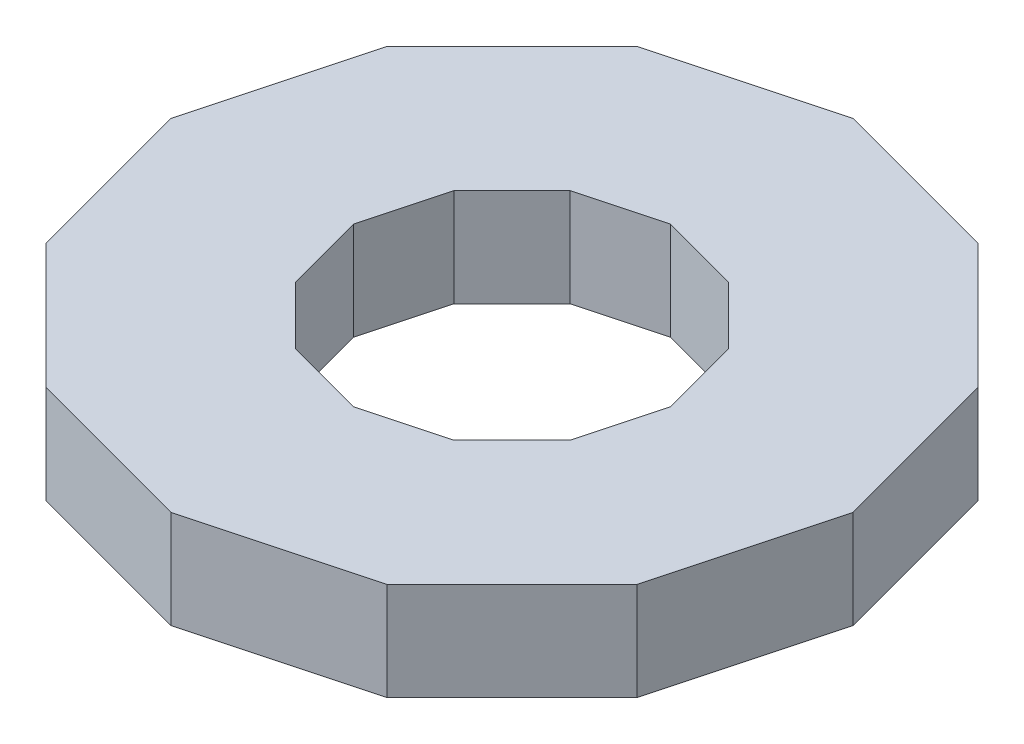
SolidWorks part; units mm, degrees
ref_plane "Front Plane" through (0, 0, 0) normal (0, 0, 1) x (1, 0, 0)
ref_plane "Top Plane" through (0, 0, 0) normal (0, 1, 0) x (1, 0, 0)
ref_plane "Right Plane" through (0, 0, 0) normal (1, 0, 0) x (0, 0, -1)
sketch "Sketch1" plane through (0, 0, 0) normal (0, 1, 0) x (1, 0, 0)
  line L0 (0, 0) -> (30.7436, 0) construction
  line L1 (30.7436, 0) -> (26.6247, 15.3718)
  line L2 (26.6247, 15.3718) -> (15.3718, 26.6247)
  line L3 (15.3718, 26.6247) -> (0, 30.7436)
  line L4 (0, 30.7436) -> (-15.3718, 26.6247)
  line L5 (-15.3718, 26.6247) -> (-26.6247, 15.3718)
  line L6 (-26.6247, 15.3718) -> (-30.7436, 0)
  line L7 (-30.7436, 0) -> (-26.6247, -15.3718)
  line L8 (-26.6247, -15.3718) -> (-15.3718, -26.6247)
  line L9 (-15.3718, -26.6247) -> (0, -30.7436)
  line L10 (0, -30.7436) -> (15.3718, -26.6247)
  line L11 (15.3718, -26.6247) -> (26.6247, -15.3718)
  line L12 (26.6247, -15.3718) -> (30.7436, 0)
  line L13 (66.2432, 0) -> (57.3683, 33.1216)
  line L14 (57.3683, 33.1216) -> (33.1216, 57.3683)
  line L15 (33.1216, 57.3683) -> (0, 66.2432)
  line L16 (0, 66.2432) -> (-33.1216, 57.3683)
  line L17 (-33.1216, 57.3683) -> (-57.3683, 33.1216)
  line L18 (-57.3683, 33.1216) -> (-66.2432, 0)
  line L19 (-66.2432, 0) -> (-57.3683, -33.1216)
  line L20 (-57.3683, -33.1216) -> (-33.1216, -57.3683)
  line L21 (-33.1216, -57.3683) -> (0, -66.2432)
  line L22 (0, -66.2432) -> (33.1216, -57.3683)
  line L23 (33.1216, -57.3683) -> (57.3683, -33.1216)
  line L24 (57.3683, -33.1216) -> (66.2432, 0)
  circle A0 centre (0, 0) radius 29.696 construction
  circle A1 centre (0, 0) radius 63.986 construction
  dimension "D1" = 34.29
  dimension "D2" = 34.29
  dimension "D3" = 63.986
extrude "Boss-Extrude1" add sketch "Sketch1" along normal blind 19.05
